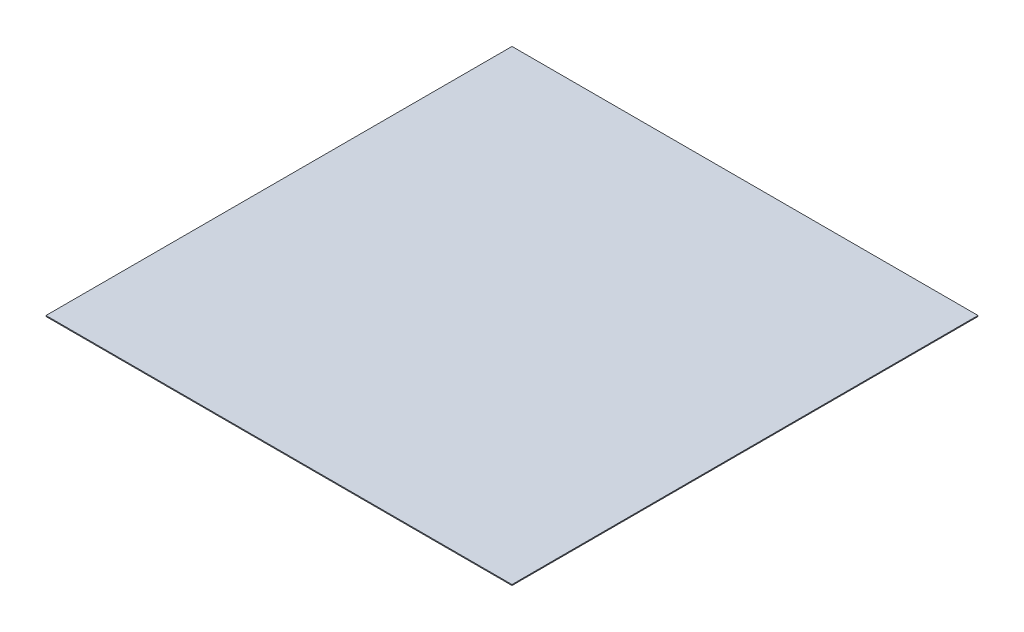
SolidWorks part; units mm, degrees
material "1023 Carbon Steel Sheet (SS)"
ref_plane "Front Plane" through (0, 0, 0) normal (0, 0, 1) x (1, 0, 0)
ref_plane "Top Plane" through (0, 0, 0) normal (0, 1, 0) x (1, 0, 0)
ref_plane "Right Plane" through (0, 0, 0) normal (1, 0, 0) x (0, 0, -1)
sketch "Sketch1" plane through (0, 0, 0) normal (0, 1, 0) x (1, 0, 0)
  line L0 (0, 0) -> (0, 1000)
  line L1 (0, 0) -> (1000, 0)
  line L3 (0, 1000) -> (1000, 1000)
  line L4 (1000, 0) -> (1000, 1000)
  point P5 (2.1306, 0)
  dimension "D1" = 1000
  dimension "D2" = 1000
extrude "Boss-Extrude1" add sketch "Sketch1" along normal blind 2 contours L1 L4 L3 L0
